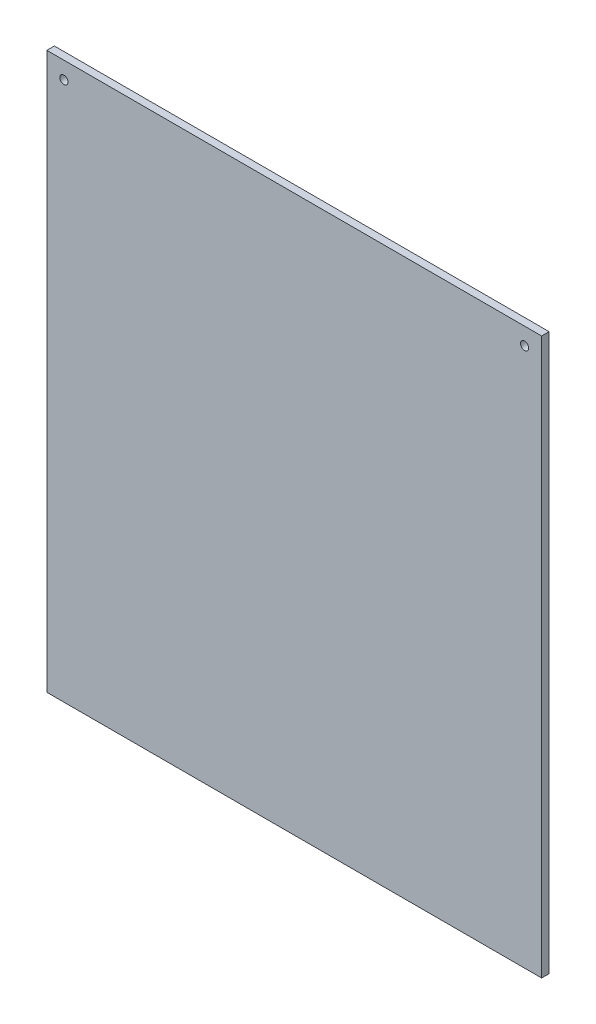
SolidWorks part; units mm, degrees
ref_plane "Front Plane" through (0, 0, 0) normal (0, 0, 1) x (1, 0, 0)
ref_plane "Top Plane" through (0, 0, 0) normal (0, 1, 0) x (1, 0, 0)
ref_plane "Right Plane" through (0, 0, 0) normal (1, 0, 0) x (0, 0, -1)
sketch "Sketch1" plane through (0, 0, 0) normal (0, 0, 1) x (1, 0, 0)
  line L0 (81.8848, 124.8822) -> (81.8848, -120.1178)
  line L1 (81.8848, 124.8822) -> (-136.1152, 124.8822)
  line L2 (81.8848, -120.1178) -> (-136.1152, -120.1178)
  line L3 (-136.1152, 124.8822) -> (-136.1152, -120.1178)
  circle A0 centre (-128.6152, 117.3822) radius 1.8
  circle A1 centre (74.3848, 117.3822) radius 1.8
  dimension "D3" = 7.5
  dimension "D1" = 245
  dimension "D2" = 218
  dimension "D4" = 7.5
  dimension "D5" = 7.5
  dimension "D6" = 7.5
extrude "Boss-Extrude1" add sketch "Sketch1" along normal blind 3.302
